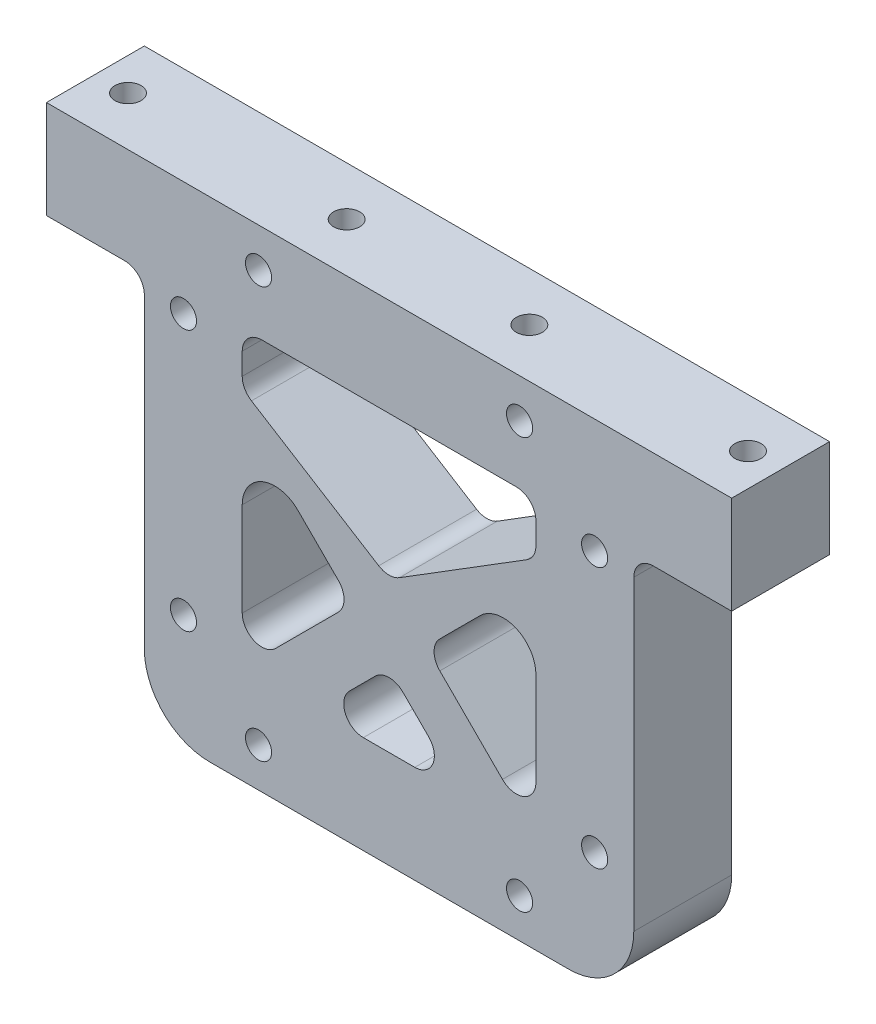
SolidWorks part; units mm, degrees
material "POM 乙缩醛共聚物"
ref_plane "前视基准面" through (0, 0, 0) normal (0, 0, 1) x (1, 0, 0)
ref_plane "上视基准面" through (0, 0, 0) normal (0, 1, 0) x (1, 0, 0)
ref_plane "右视基准面" through (0, 0, 0) normal (1, 0, 0) x (0, 0, -1)
sketch "草图1" plane through (0, 0, 0) normal (0, 0, 1) x (1, 0, 0)
  line L1 (-37.5, 37.5) -> (37.5, 37.5)
  line L2 (-37.5, 37.5) -> (-37.5, -37.5)
  line L3 (-37.5, -37.5) -> (37.5, -37.5)
  line L4 (37.5, 37.5) -> (37.5, -37.5)
  line L5 (-37.5, 37.5) -> (37.5, -37.5) construction
  line L6 (-37.5, -37.5) -> (37.5, 37.5) construction
  point P0 (0, 0)
  dimension "D1" = 75
  dimension "D2" = 75
extrude "凸台-拉伸1" add sketch "草图1" along normal blind 15
sketch "草图2" plane through (0, 0, 15) normal (0, 0, 1) x (1, 0, 0)
  line L0 (37.5, 37.5) -> (-37.5, 37.5) construction
  line L1 (-20, 31.5) -> (20, 31.5) construction
  line L2 (-20, 31.5) -> (-20, -31.5) construction
  line L3 (-20, -31.5) -> (20, -31.5) construction
  line L4 (20, 31.5) -> (20, -31.5) construction
  line L5 (-20, 31.5) -> (20, -31.5) construction
  line L6 (-20, -31.5) -> (20, 31.5) construction
  circle A0 centre (-20, 31.5) radius 2
  circle A1 centre (20, 31.5) radius 2
  circle A2 centre (20, -31.5) radius 2
  circle A3 centre (-20, -31.5) radius 2
  point P0 (0, 0)
  dimension "D3" = 4
  dimension "D1" = 6
  dimension "D2" = 40
extrude "切除-拉伸1" cut sketch "草图2" against normal blind 15
sketch "草图3" plane through (0, 0, 15) normal (0, 0, 1) x (1, 0, 0)
  line L0 (37.5, -37.5) -> (37.5, 37.5) construction
  line L1 (-31.5, 20) -> (31.5, 20) construction
  line L2 (-31.5, 20) -> (-31.5, -20) construction
  line L3 (-31.5, -20) -> (31.5, -20) construction
  line L4 (31.5, 20) -> (31.5, -20) construction
  line L5 (-31.5, 20) -> (31.5, -20) construction
  line L6 (-31.5, -20) -> (31.5, 20) construction
  circle A0 centre (-31.5, 20) radius 2
  circle A1 centre (-31.5, -20) radius 2
  circle A2 centre (31.5, -20) radius 2
  circle A3 centre (31.5, 20) radius 2
  point P0 (0, 0)
  dimension "D3" = 4
  dimension "D1" = 40
  dimension "D2" = 6
extrude "切除-拉伸2" cut sketch "草图3" against normal through all
fillet "圆角1" radius 10 2 edges at (37.5, -37.5, 7.5) (-37.5, -37.5, 7.5)
sketch "草图4" plane through (0, 0, 15) normal (0, 0, 1) x (1, 0, 0)
  line L0 (37.5, 37.5) -> (-37.5, 37.5) construction
  line L1 (-22.5, 22.5) -> (22.5, 22.5)
  line L2 (-22.5, 22.5) -> (-22.5, -22.5)
  line L3 (-22.5, -22.5) -> (22.5, -22.5)
  line L4 (22.5, 22.5) -> (22.5, -22.5)
  line L5 (-22.5, 22.5) -> (22.5, -22.5) construction
  line L6 (-22.5, -22.5) -> (22.5, 22.5) construction
  line L7 (-37.5, 37.5) -> (-37.5, -27.5) construction
  line L8 (-22.5, 22.5) -> (22.5, -22.5)
  line L9 (22.5, 22.5) -> (-22.5, -22.5)
  line L10 (-22.5, 11.1863) -> (11.1863, -22.5)
  line L11 (-11.1863, -22.5) -> (22.5, 11.1863)
  point P0 (0, 0)
  point P10 (-9.7779, -22.5)
  point P11 (-22.5, 9.7623)
  point P12 (9.9308, -22.5)
  point P13 (22.5, 9.7721)
  point P18 (9.7972, -22.5)
  dimension "D1" = 15
  dimension "D2" = 15
  dimension "D3" = 8
  dimension "D4" = 8
extrude "切除-拉伸4" cut sketch "草图4" against normal blind 15 contours L10 L2 L9 | L11 L3 L10 | L11 L8 L4
sketch "草图5" plane through (0, 0, 15) normal (0, 0, 1) x (1, 0, 0)
  line L0 (0, 37.5) -> (0, -37.5) construction
  line L1 (37.5, 37.5) -> (-37.5, 37.5) construction
  line L2 (-27.5, -37.5) -> (27.5, -37.5) construction
  line L3 (22.5, 22.5) -> (-22.5, 22.5)
  line L6 (-22.5, 22.5) -> (-22.5, 14.5)
  line L7 (22.5, 22.5) -> (22.5, 14.5)
  line L8 (-22.5, 14.5) -> (0, 0.5)
  line L9 (22.5, 14.5) -> (0, 0.5)
  line L10 (37.5, -27.5) -> (37.5, 37.5) construction
  point P9 (0, 22.5)
  point P14 (22.5, 17.7319)
  dimension "D2" = 15
  dimension "D1" = 15
  dimension "D3" = 8
  dimension "D4" = 22
extrude "切除-拉伸5" cut sketch "草图5" against normal through all
fillet "圆角3" radius 5 2 edges at (22.5, 11.1863, 7.5) (-22.5, 11.1863, 7.5)
fillet "圆角4" radius 3 12 edges at (-11.1863, -22.5, 7.5) (11.1863, -22.5, 7.5) (0, -11.3137, 7.5) (-22.5, -22.5, 7.5) (-5.6569, -5.6569, 7.5) (5.6569, -5.6569, 7.5) (22.5, -22.5, 7.5) (0, 0.5, 7.5) (22.5, 14.5, 7.5) (22.5, 22.5, 7.5) (-22.5, 22.5, 7.5) (-22.5, 14.5, 7.5)
sketch "草图6" plane through (0, 37.5, 0) normal (0, 1, 0) x (1, 0, 0)
  line L0 (-37.5, -7.5) -> (37.5, -7.5) construction
  line L3 (0, 0) -> (0, -15) construction
  line L4 (37.5, -15) -> (-37.5, -15) construction
  line L5 (-37.5, -15) -> (-37.5, 0) construction
  line L6 (37.5, -15) -> (37.5, 0) construction
  circle A0 centre (-14, -7.5) radius 2
  circle A1 centre (14, -7.5) radius 2
  point P2 (0, 0)
  point P3 (-37.5, -7.5)
  point P15 (-27.5, -7.5)
  point P16 (37.5, -7.5)
  dimension "D1" = 14
  dimension "D2" = 4
extrude "切除-拉伸6" cut sketch "草图6" against normal blind 15
sketch "草图8" plane through (0, 0, 15) normal (0, 0, 1) x (1, 0, 0)
  line L0 (0, 37.5) -> (0, -37.5) construction
  line L1 (37.5, 37.5) -> (-37.5, 37.5) construction
  line L2 (-27.5, -37.5) -> (27.5, -37.5) construction
  line L3 (-37.5, 37.5) -> (-52.5, 37.5)
  line L4 (37.5, 37.5) -> (52.5, 37.5)
  line L5 (-52.5, 37.5) -> (-52.5, 22.5)
  line L6 (52.5, 37.5) -> (52.5, 22.5)
  line L7 (-52.5, 22.5) -> (-37.5, 22.5)
  line L8 (-37.5, 37.5) -> (-37.5, -27.5) construction
  line L9 (52.5, 22.5) -> (37.5, 22.5)
  line L10 (-37.5, 22.5) -> (-37.5, 37.5)
  line L11 (37.5, 22.5) -> (37.5, 37.5)
  dimension "D1" = 15
  dimension "D2" = 15
extrude "凸台-拉伸2" add sketch "草图8" against normal up to surface (15 mm away) up to face at (0, 14.6968, 0)
fillet "圆角5" radius 3 2 edges at (37.5, 22.5, 7.5) (-37.5, 22.5, 7.5)
sketch "草图9" plane through (0, 37.5, 0) normal (0, 1, 0) x (1, 0, 0)
  line L0 (-52.5, -7.5) -> (52.5, -7.5) construction
  line L1 (-52.5, 0) -> (-52.5, -15) construction
  line L2 (52.5, 0) -> (52.5, -15) construction
  line L3 (0, 0) -> (0, -15) construction
  line L4 (52.5, -15) -> (-52.5, -15) construction
  circle A0 centre (-47.5, -7.5) radius 2
  circle A1 centre (47.5, -7.5) radius 2
  dimension "D1" = 5
  dimension "D2" = 4
extrude "切除-拉伸8" cut sketch "草图9" against normal through all
